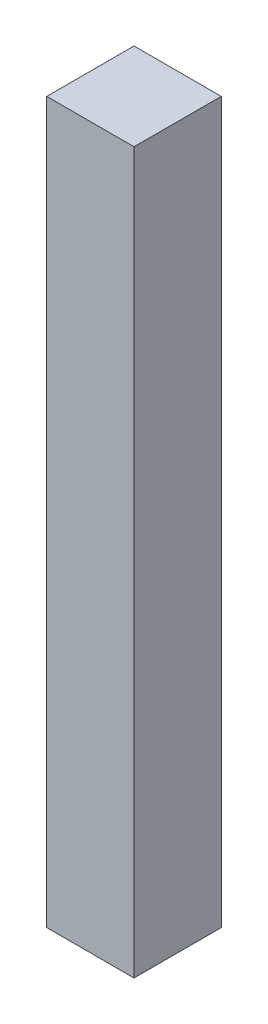
SolidWorks part; units mm, degrees
ref_plane "Front Plane" through (0, 0, 0) normal (0, 0, 1) x (1, 0, 0)
ref_plane "Top Plane" through (0, 0, 0) normal (0, 1, 0) x (1, 0, 0)
ref_plane "Right Plane" through (0, 0, 0) normal (1, 0, 0) x (0, 0, -1)
sketch "Sketch2" plane through (0, 0, 0) normal (0, 1, 0) x (1, 0, 0)
  line L1 (-20, 20) -> (20, 20)
  line L2 (-20, 20) -> (-20, -20)
  line L3 (-20, -20) -> (20, -20)
  line L4 (20, 20) -> (20, -20)
  dimension "D1" = 40
  dimension "D2" = 40
extrude "Boss-Extrude1" add sketch "Sketch2" along normal blind 330
